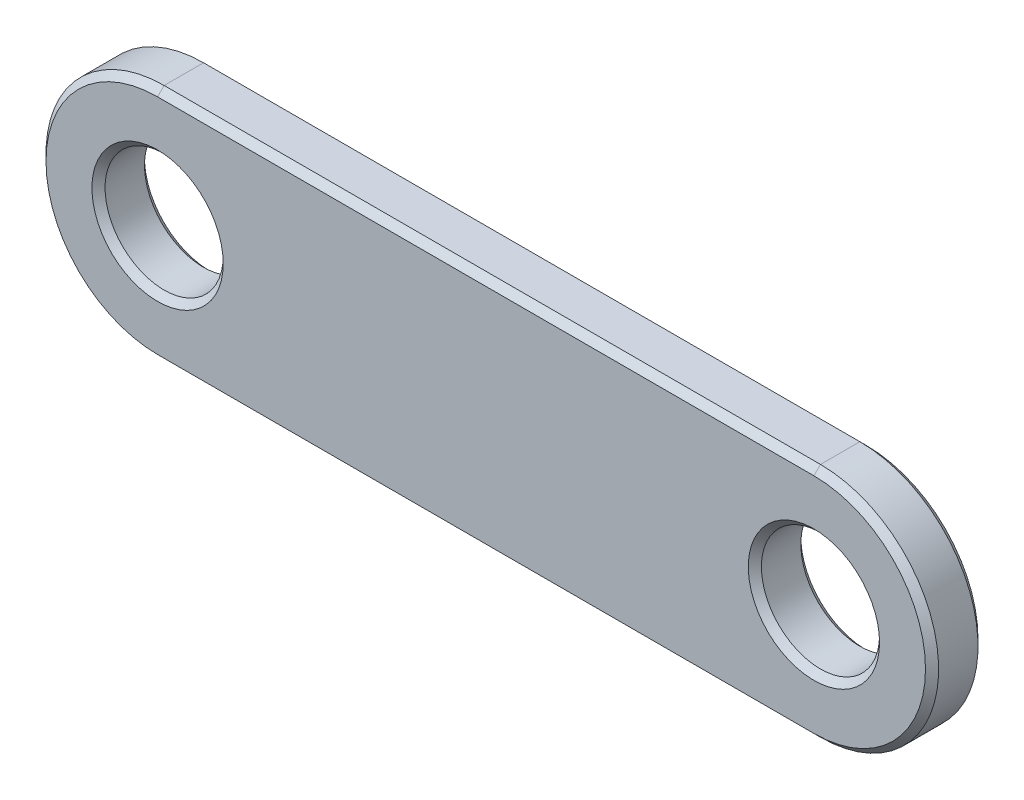
SolidWorks part; units mm, degrees
material "Cast Alloy Steel"
ref_plane "Front Plane" through (0, 0, 0) normal (0, 0, 1) x (1, 0, 0)
ref_plane "Top Plane" through (0, 0, 0) normal (0, 1, 0) x (1, 0, 0)
ref_plane "Right Plane" through (0, 0, 0) normal (1, 0, 0) x (0, 0, -1)
sketch "Sketch1" plane through (0, 0, 0) normal (0, 0, 1) x (1, 0, 0)
  line L0 (-63.5, 0) -> (0, 0) construction
  line L1 (-63.5, 0) -> (0, 0) construction
  line L2 (-63.5, 11.43) -> (0, 11.43)
  line L3 (-63.5, -11.43) -> (0, -11.43)
  circle A0 centre (0, 0) radius 5.715
  circle A1 centre (-63.5, 0) radius 5.715
  arc A2 (-63.5, 11.43) -> (-63.5, -11.43) centre (-63.5, 0) ccw
  arc A3 (0, -11.43) -> (0, 11.43) centre (0, 0) ccw
  point P5 (-31.75, 0)
  dimension "D1" = 11.43
  dimension "D2" = 63.5
  dimension "D3" = 22.86
extrude "Boss-Extrude1" add sketch "Sketch1" along normal blind 5.08
chamfer "Chamfer1" distance 0.635 angle 45 12 edges at (-57.785, 0, 0) (5.715, 0, 0) (-31.75, -11.43, 0) (11.43, 0, 0) (-31.75, 11.43, 0) (-74.93, 0, 0) (-57.785, 0, 5.08) (-31.75, 11.43, 5.08) (11.43, 0, 5.08) (-31.75, -11.43, 5.08) (-74.93, 0, 5.08) (5.715, 0, 5.08)
